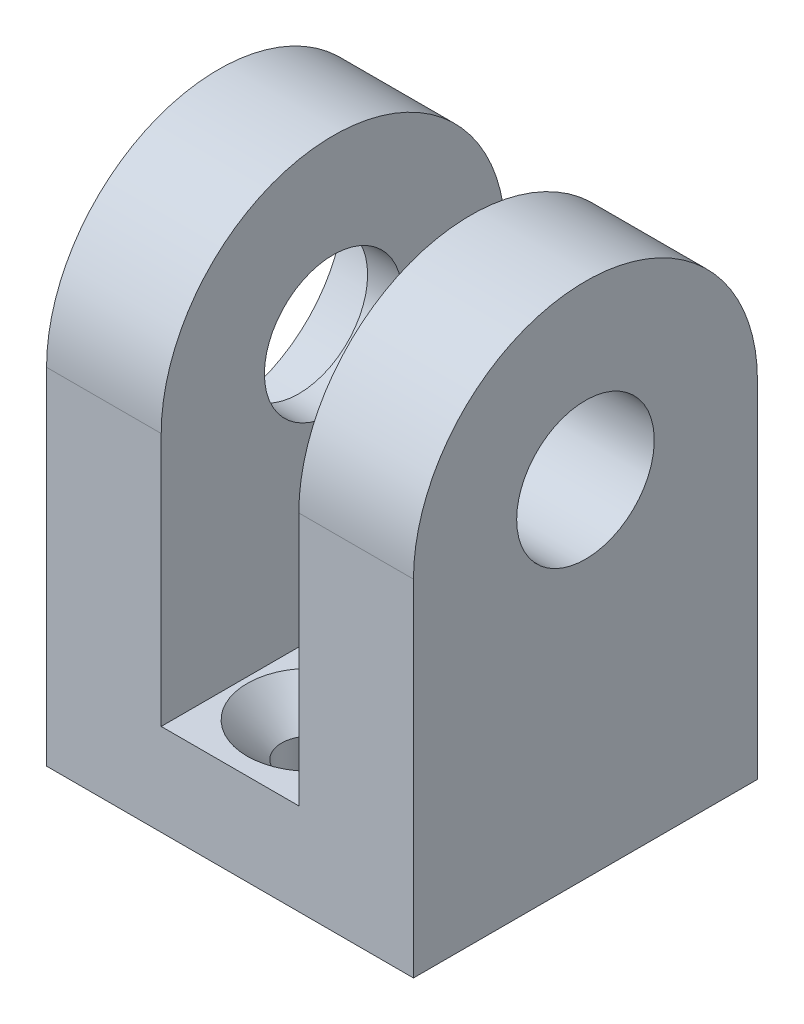
SolidWorks part; units mm, degrees
material "1060 合金"
ref_plane "前视基准面" through (0, 0, 0) normal (0, 0, 1) x (1, 0, 0)
ref_plane "上视基准面" through (0, 0, 0) normal (0, 1, 0) x (1, 0, 0)
ref_plane "右视基准面" through (0, 0, 0) normal (1, 0, 0) x (0, 0, -1)
sketch "草图1" plane through (0, 0, 0) normal (0, 1, 0) x (1, 0, 0)
  line L1 (-16, 15) -> (16, 15)
  line L2 (-16, 15) -> (-16, -15)
  line L3 (-16, -15) -> (16, -15)
  line L4 (16, 15) -> (16, -15)
  point P4 (0, 15)
  point P6 (16, 0)
  dimension "D1" = 30
  dimension "D2" = 32
extrude "凸台-拉伸1" add sketch "草图1" along normal blind 8
sketch "草图2" plane through (-16, 0, 0) normal (-1, 0, 0) x (0, 0, 1)
  line L0 (-15, 8) -> (-15, 0) construction
  line L1 (15, 0) -> (-15, 0)
  line L2 (15, 0) -> (15, 30.125)
  line L4 (-15, 0) -> (-15, 30.125)
  arc A0 (15, 30.125) -> (-15, 30.125) centre (0, 30.125) ccw
  circle A1 centre (0, 30.125) radius 6
  dimension "D2" = 12
  dimension "D1" = 30.125
extrude "凸台-拉伸2" add sketch "草图2" against normal blind 10
sketch "草图4" plane through (-6, 0, 0) normal (-1, 0, 0) x (0, 0, 1)
  circle A0 centre (0, 30.125) radius 11
  dimension "D1" = 22
extrude "切除-拉伸1" cut sketch "草图4" against normal blind 7 from surface at 10 starting at face at (-16, 18.8125, 0)
mirror "镜向1" about plane through (0, 0, 0) normal (1, 0, 0) of "凸台-拉伸2"
sketch "草图5" plane through (0, 8, 0) normal (0, 1, 0) x (1, 0, 0)
  line L0 (-6, 0) -> (6, 0) construction
  line L1 (-6, -15) -> (-6, 15) construction
  line L2 (6, 15) -> (6, -15) construction
  circle A0 centre (0, 8) radius 2.5
  circle A1 centre (0, -8) radius 2.5
  dimension "D1" = 5
  dimension "D2" = 16
extrude "切除-拉伸2" cut sketch "草图5" against normal through all
chamfer "倒角1" distance 3 angle 45 2 edges at (0, 8, 10.5) (0, 8, -5.5)
sketch "草图6" plane through (16, 0, 0) normal (1, 0, 0) x (0, 0, -1)
  circle A1 centre (0, 30.125) radius 5
  circle A2 centre (0, 30.125) radius 6 construction
  dimension "D1" = 10
